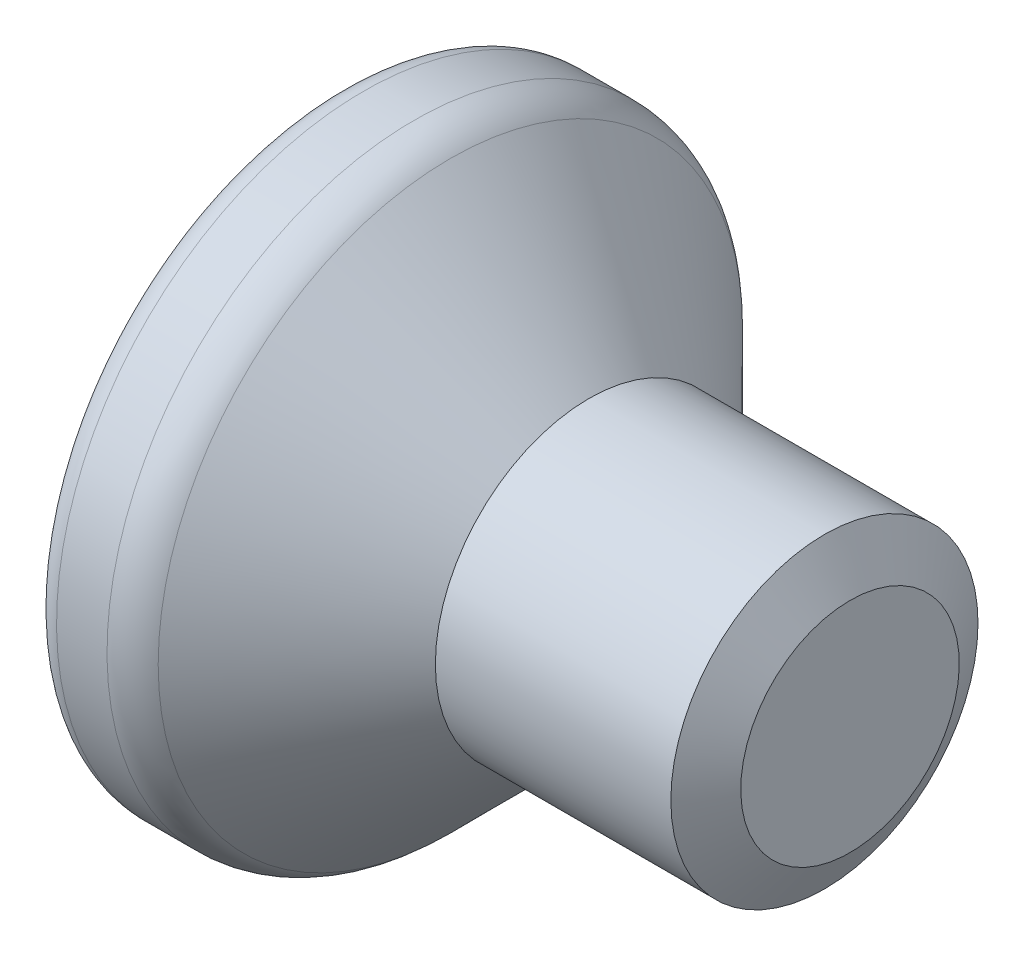
SolidWorks part; units mm, degrees
ref_plane "前视基准面" through (0, 0, 0) normal (0, 0, 1) x (1, 0, 0)
ref_plane "上视基准面" through (0, 0, 0) normal (0, 1, 0) x (1, 0, 0)
ref_plane "右视基准面" through (0, 0, 0) normal (1, 0, 0) x (0, 0, -1)
sketch "草图1" plane through (0, 0, 0) normal (0, 0, 1) x (1, 0, 0)
  line L0 (5, 0) -> (-5, 0)
  line L1 (-5, 0) -> (-5, 6)
  line L2 (-5, 6) -> (-3.1, 6)
  line L3 (-3.1, 6) -> (-0.1, 3)
  line L4 (-0.1, 3) -> (5, 3)
  line L5 (5, 3) -> (5, 0)
  point P5 (0, 0)
  dimension "D1" = 4.9
  dimension "D2" = 6
  dimension "D3" = 3
  dimension "D4" = 45
  dimension "D5" = 10
revolve "旋转1" add sketch "草图1" angle 360 about L0
fillet "圆角1" radius 0.5 1 edges at (-5, 6, 0)
fillet "圆角2" radius 1 1 edges at (-3.1, 6, 0)
sketch "草图2" plane through (-5, 0, 0) normal (-1, 0, 0) x (0, 0, 1)
  line L1 (0, 2.3094) -> (-2, 1.1547)
  line L2 (-2, 1.1547) -> (-2, -1.1547)
  line L3 (-2, -1.1547) -> (0, -2.3094)
  line L4 (0, -2.3094) -> (2, -1.1547)
  line L5 (2, -1.1547) -> (2, 1.1547)
  line L6 (2, 1.1547) -> (0, 2.3094)
  circle A0 centre (0, 0) radius 2 construction
  dimension "D1" = 4
extrude "切除-拉伸1" cut sketch "草图2" against normal blind 2.5
chamfer "倒角1" distance 0.5 angle 60 1 edges at (5, 3, 0)
